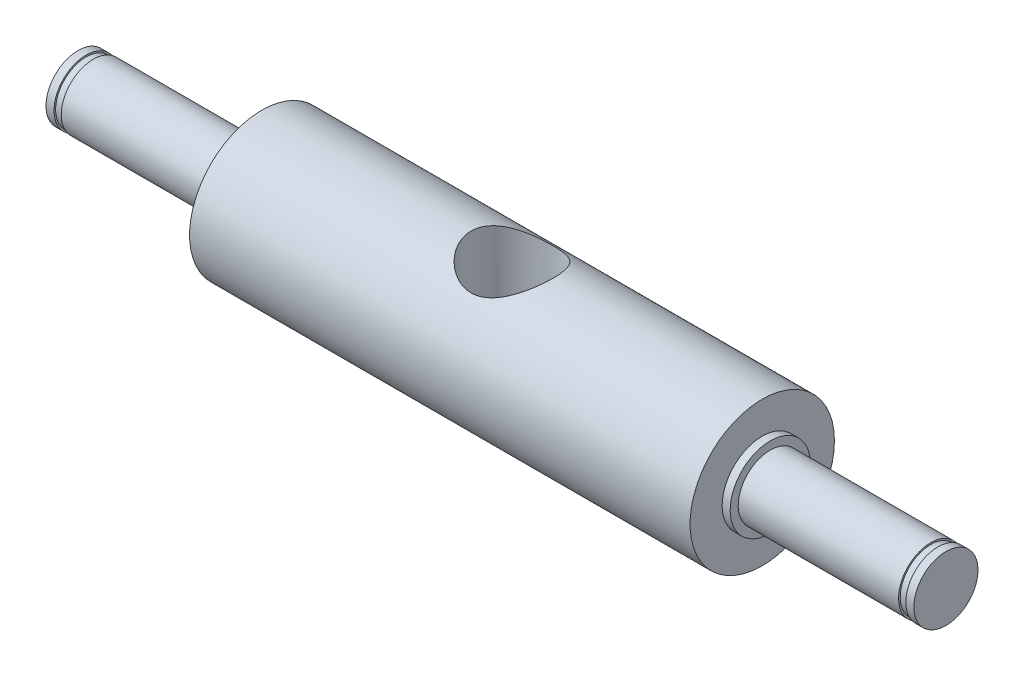
SolidWorks part; units mm, degrees
material "1060 Alloy"
ref_plane "Front Plane" through (0, 0, 0) normal (0, 0, 1) x (1, 0, 0)
ref_plane "Top Plane" through (0, 0, 0) normal (0, 1, 0) x (1, 0, 0)
ref_plane "Right Plane" through (0, 0, 0) normal (1, 0, 0) x (0, 0, -1)
sketch "Sketch1" plane through (0, 0, 0) normal (1, 0, 0) x (0, 0, -1)
  circle A0 centre (0, 0) radius 9
  dimension "D1" = 18
extrude "Boss-Extrude1" add sketch "Sketch1" along normal mid plane 62.4
sketch "Sketch2" plane through (0, 0, 0) normal (0, 1, 0) x (1, 0, 0)
  circle A0 centre (0, 0) radius 5.1
  dimension "D1" = 10.2
extrude "Cut-Extrude1" cut sketch "Sketch2" against normal through all both and the other way through all
sketch "Sketch6" plane through (0, 0, 0) normal (0, 0, 1) x (1, 0, 0)
  line L0 (31.2, 0) -> (31.2, 5)
  line L1 (31.2, -9) -> (31.2, 9) construction
  line L2 (32.2, 4) -> (52.2, 4)
  line L3 (52.2, 4) -> (52.2, 3.8)
  line L4 (52.2, 3.8) -> (53.1, 3.8)
  line L5 (53.1, 3.8) -> (53.1, 4)
  line L6 (53.1, 4) -> (54.1, 4)
  line L7 (54.1, 4) -> (54.1, 0)
  line L8 (54.1, 0) -> (31.2, 0)
  line L9 (32.2, 4) -> (32.2, 5)
  line L10 (32.2, 5) -> (31.2, 5)
  dimension "D1" = 4
  dimension "D2" = 5
  dimension "D3" = 3.8
  dimension "D4" = 0.9
  dimension "D5" = 1
  dimension "D6" = 20
  dimension "D7" = 1
revolve "Revolve1" add sketch "Sketch6" angle 360 about L8
mirror "Mirror1" about plane through (0, 0, 0) normal (1, 0, 0) of "Revolve1"
sketch "Sketch7" plane through (0, 0, 0) normal (0, 1, 0) x (1, 0, 0)
  circle A0 centre (0, 0) radius 5.25
  circle A1 centre (0, 0) radius 3
  dimension "D1" = 10.5
  dimension "D2" = 6
extrude "Boss-Extrude2" add sketch "Sketch7" against normal blind 5
